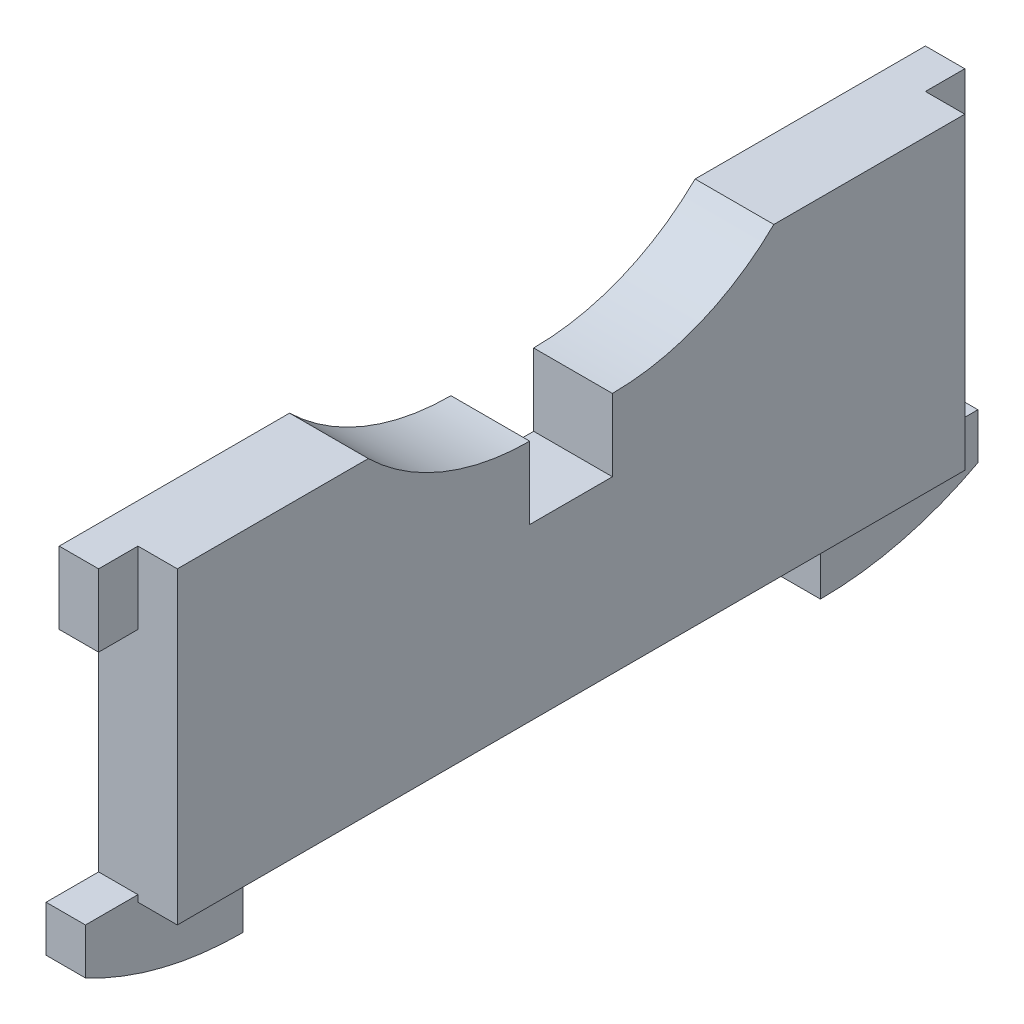
SolidWorks part; units mm, degrees
ref_plane "Front Plane" through (0, 0, 0) normal (0, 0, 1) x (1, 0, 0)
ref_plane "Top Plane" through (0, 0, 0) normal (0, 1, 0) x (1, 0, 0)
ref_plane "Right Plane" through (0, 0, 0) normal (1, 0, 0) x (0, 0, -1)
sketch "Sketch1" plane through (0, 0, 0) normal (1, 0, 0) x (0, 0, -1)
  line L0 (-3.15, 0) -> (3.15, 0)
  line L1 (3.15, 0) -> (3.15, 5.5)
  line L2 (3.15, 5.5) -> (15.45, 5.5) construction
  line L3 (15.45, 5.5) -> (15.45, 10.5) construction
  line L4 (15.45, 10.5) -> (30, 10.5)
  line L5 (30, 10.5) -> (30, -13)
  line L6 (30, -13) -> (-30, -13)
  line L7 (0, -13) -> (0, 0) construction
  line L8 (-15.45, 5.5) -> (-15.45, 10.5) construction
  line L9 (-3.15, 5.5) -> (-15.45, 5.5) construction
  line L10 (-30, 10.5) -> (-30, -13)
  line L11 (-15.45, 10.5) -> (-30, 10.5)
  line L12 (-3.15, 0) -> (-3.15, 5.5)
  arc A0 (3.15, 5.5) -> (15.45, 10.5) centre (3.15, 23.129) ccw
  arc A1 (-3.15, 5.5) -> (-15.45, 10.5) centre (-3.15, 23.129) cw
  point P4 (0, 0)
  dimension "D1" = 6.3
  dimension "D2" = 5.5
  dimension "D3" = 12.3
  dimension "D4" = 5
  dimension "D5" = 60
  dimension "D6" = 23.5
extrude "Boss-Extrude1" add sketch "Sketch1" along normal blind 3
sketch "Sketch2" plane through (0, 0, 0) normal (-1, 0, 0) x (0, 0, 1)
  line L0 (30, -13) -> (-30, -13) construction
  line L1 (30, 10.5) -> (30, -13) construction
  line L2 (15.45, 10.5) -> (30, 10.5) construction
  line L3 (3.15, 0) -> (3.15, 5.5) construction
  line L4 (-3.15, 0) -> (3.15, 0) construction
  line L5 (-3.15, 5.5) -> (-3.15, 0) construction
  line L6 (-30, 10.5) -> (-15.45, 10.5) construction
  line L7 (-30, -13) -> (-30, 10.5) construction
  line L8 (30, -13) -> (-30, -13)
  line L9 (30, 10.5) -> (30, -13)
  line L10 (15.45, 10.5) -> (30, 10.5)
  line L11 (3.15, 0) -> (3.15, 5.5)
  line L12 (-3.15, 0) -> (3.15, 0)
  line L13 (-3.15, 5.5) -> (-3.15, 0)
  line L14 (-30, 10.5) -> (-15.45, 10.5)
  line L15 (-30, -13) -> (-30, 10.5)
  line L16 (-22, -13) -> (22, -13)
  line L17 (22, -13) -> (22, -19)
  line L18 (30, -13) -> (34, -13) construction
  line L19 (34, -13) -> (34, -16)
  line L20 (34, -13) -> (34, -12.5)
  line L21 (34, -12.5) -> (30, -12.5)
  line L22 (22, -13) -> (30, -13)
  line L23 (30, -12.5) -> (30, -13)
  line L24 (0, 0) -> (0, -12.5531) construction
  line L25 (-22, -13) -> (-22, -19)
  line L26 (-34, -13) -> (-34, -16)
  line L27 (-34, -13) -> (-34, -12.5)
  line L28 (-34, -12.5) -> (-30, -12.5)
  line L29 (-30, 10.5) -> (-30, -13)
  line L30 (-15.45, 10.5) -> (-30, 10.5)
  line L31 (-3.15, 0) -> (-3.15, 5.5)
  line L32 (3.15, 5.5) -> (3.15, 0)
  line L33 (30, 10.5) -> (15.45, 10.5)
  line L34 (30, -13) -> (30, 10.5)
  line L35 (30, 10.5) -> (33, 10.5)
  line L36 (33, 10.5) -> (33, 5)
  line L37 (33, 5) -> (30, 5)
  line L38 (30, 5) -> (30, 10.5)
  line L39 (-30, 10.5) -> (-33, 10.5)
  line L40 (-30, 10.5) -> (-30, -13)
  line L41 (-33, 5) -> (-30, 5)
  line L42 (-33, 10.5) -> (-33, 5)
  line L43 (-30, 10.5) -> (-30, 5)
  arc A0 (3.15, 5.5) -> (15.45, 10.5) centre (3.15, 23.129) ccw construction
  arc A1 (-15.45, 10.5) -> (-3.15, 5.5) centre (-3.15, 23.129) ccw construction
  arc A2 (3.15, 5.5) -> (15.45, 10.5) centre (3.15, 23.129) ccw
  arc A3 (-15.45, 10.5) -> (-3.15, 5.5) centre (-3.15, 23.129) ccw
  arc A4 (22, -19) -> (34, -16) centre (22, 6.5) ccw
  arc A5 (-22, -19) -> (-34, -16) centre (-22, 6.5) cw
  arc A6 (-3.15, 5.5) -> (-15.45, 10.5) centre (-3.15, 23.129) cw
  arc A7 (15.45, 10.5) -> (3.15, 5.5) centre (3.15, 23.129) cw
  point P15 (0, -13)
  line M21 (-30, -13) -> (30, -13)
  line M22 (30, -13) -> (30, 10.5)
  dimension "D1" = 44
  dimension "D2" = 4
  dimension "D3" = 3
  dimension "D4" = 17.5
  dimension "D5" = 6
  dimension "D6" = 5.5
  dimension "D7" = 3
extrude "Boss-Extrude2" add sketch "Sketch2" along normal blind 3 contours A5 L25 L15 L28 L27 L26 M21 | L17 A4 L19 L20 L21 M22 M21 | L43 L41 L42 L39 | L35 L36 L37 L38
